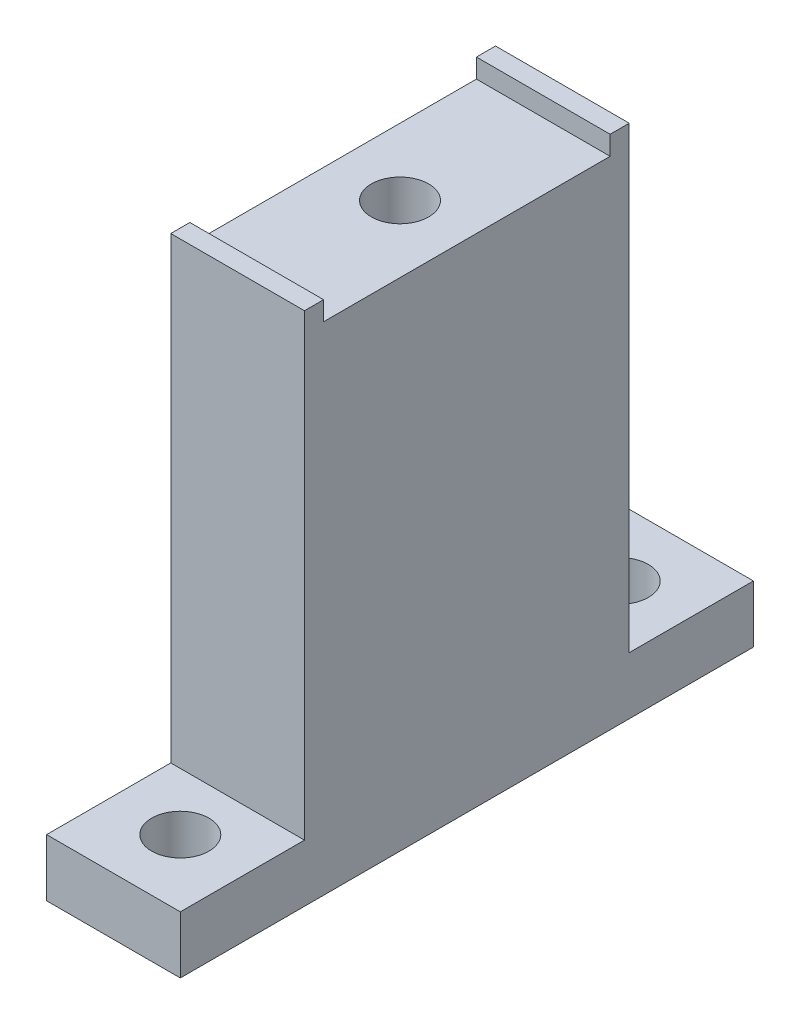
SolidWorks part; units mm, degrees
ref_plane "Front Plane" through (0, 0, 0) normal (0, 0, 1) x (1, 0, 0)
ref_plane "Top Plane" through (0, 0, 0) normal (0, 1, 0) x (1, 0, 0)
ref_plane "Right Plane" through (0, 0, 0) normal (1, 0, 0) x (0, 0, -1)
sketch "Sketch1" plane through (0, 0, 0) normal (0, 1, 0) x (1, 0, 0)
  line L1 (0, 0) -> (-7, 0)
  line L2 (0, 0) -> (0, 30)
  line L3 (0, 30) -> (-7, 30)
  line L4 (-7, 0) -> (-7, 30)
  dimension "D1" = 30
  dimension "D2" = 7
extrude "Boss-Extrude1" add sketch "Sketch1" along normal blind 3
sketch "Sketch2" plane through (0, 3, 0) normal (0, 1, 0) x (1, 0, 0)
  line L0 (0, 0) -> (0, 30) construction
  line L1 (0, 30) -> (-7, 30) construction
  line L2 (-7, 0) -> (0, 0) construction
  circle A0 centre (-3.5, 26.5) radius 1.5
  circle A1 centre (-3.5, 3.5) radius 1.5
  dimension "D1" = 3
  dimension "D4" = 3
  dimension "D2" = 3.5
  dimension "D3" = 3.5
  dimension "D5" = 3.5
  dimension "D6" = 3.5
extrude "Cut-Extrude1" cut sketch "Sketch2" against normal blind 3 contours A0 | A1
sketch "Sketch3" plane through (0, 3, 0) normal (0, 1, 0) x (1, 0, 0)
  line L0 (-7, 30) -> (-7, 0) construction
  line L1 (-7, 15) -> (0, 15)
  line L2 (-7, 15) -> (-7, 23.5)
  line L3 (-7, 23.5) -> (0, 23.5)
  line L4 (0, 15) -> (0, 23.5)
  line L5 (0, 0) -> (0, 30) construction
  line L7 (-7, 15) -> (0, 15)
  line L8 (-7, 15) -> (-7, 6.5)
  line L9 (-7, 6.5) -> (0, 6.5)
  line L10 (0, 15) -> (0, 6.5)
  line M6 (0, 0) -> (0, 30)
  line M8 (-7, 30) -> (-7, 0)
  dimension "D1" = 8.5
  dimension "D2" = 8.5
extrude "Boss-Extrude2" add sketch "Sketch3" along normal blind 23 contours L3 L1 M8 M6 | L9 L1 M8 M6
sketch "Sketch4" plane through (0, 26, 0) normal (0, 1, 0) x (1, 0, 0)
  line L1 (-7, 23.5) -> (-7, 6.5) construction
  line L2 (-7, 6.5) -> (0, 6.5) construction
  circle A0 centre (-3.5, 15) radius 1.5
  dimension "D1" = 3
  dimension "D2" = 3.5
  dimension "D3" = 8.5
extrude "Cut-Extrude3" cut sketch "Sketch4" against normal blind 12
sketch "Sketch5" plane through (0, 26, 0) normal (0, 1, 0) x (1, 0, 0)
  line L0 (0, 6.5) -> (0, 23.5) construction
  line L1 (-7, 23.5) -> (0, 23.5)
  line L2 (-7, 23.5) -> (-7, 22.5)
  line L3 (-7, 22.5) -> (0, 22.5)
  line L4 (0, 23.5) -> (0, 22.5)
  line L6 (-7, 6.5) -> (0, 6.5)
  line L7 (-7, 6.5) -> (-7, 7.5)
  line L8 (-7, 7.5) -> (0, 7.5)
  line L9 (0, 6.5) -> (0, 7.5)
  dimension "D1" = 1
  dimension "D2" = 1
extrude "Boss-Extrude3" add sketch "Sketch5" along normal blind 1
